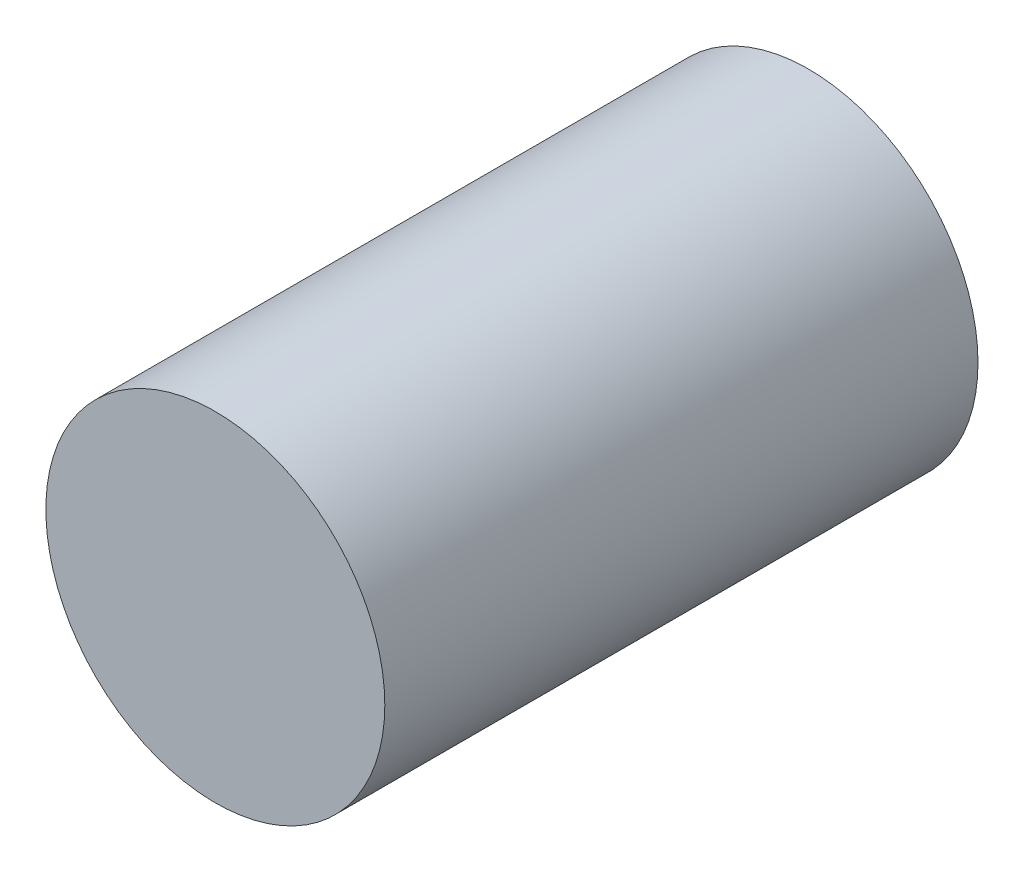
SolidWorks part; units mm, degrees
ref_plane "Front Plane" through (0, 0, 0) normal (0, 0, 1) x (1, 0, 0)
ref_plane "Top Plane" through (0, 0, 0) normal (0, 1, 0) x (1, 0, 0)
ref_plane "Right Plane" through (0, 0, 0) normal (1, 0, 0) x (0, 0, -1)
sketch "Sketch1" plane through (0, 0, 0) normal (0, 0, 1) x (1, 0, 0)
  circle A0 centre (-400, -1650) radius 200
extrude "Boss-Extrude1" add sketch "Sketch1" along normal blind 700 from offset 350
